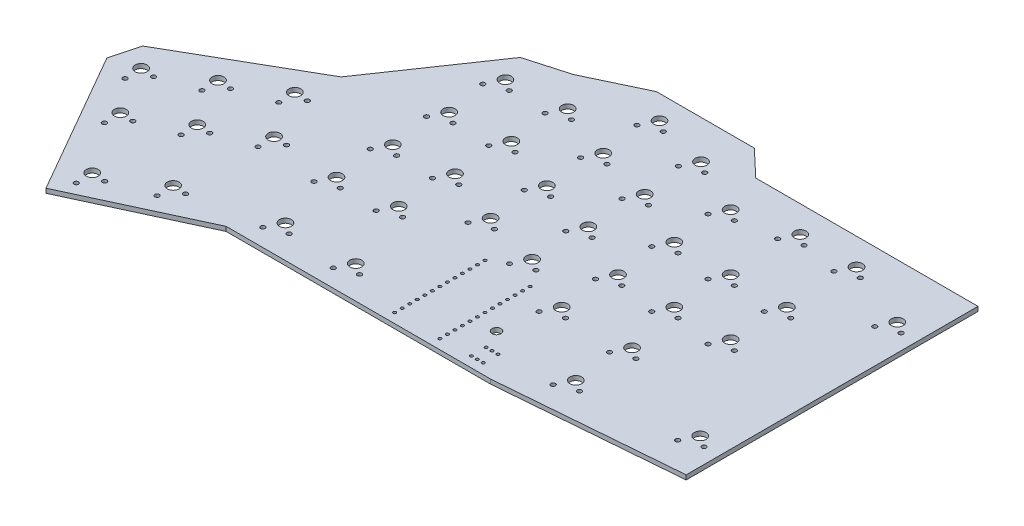
SolidWorks part; units mm, degrees
ref_plane "Front Plane" through (0, 0, 0) normal (0, 0, 1) x (1, 0, 0)
ref_plane "Top Plane" through (0, 0, 0) normal (0, 1, 0) x (1, 0, 0)
ref_plane "Right Plane" through (0, 0, 0) normal (1, 0, 0) x (0, 0, -1)
sketch "Main" plane through (0, 0, 0) normal (0, 1, 0) x (1, 0, 0)
  line L0 (6.46, 3.92) -> (12.81, 6.46) construction
  line L1 (0, 0) -> (18, 0) construction
  line L2 (0, 0) -> (0, 18) construction
  line L3 (0, 18) -> (18, 18) construction
  line L4 (18, 0) -> (18, 18) construction
  line L5 (2, 16) -> (16, 16)
  line L6 (2, 16) -> (2, 2)
  line L7 (2, 2) -> (16, 2)
  line L8 (16, 16) -> (16, 2)
  line L18 (9, 9) -> (6.46, 3.92) construction
  line L20 (9, 9) -> (12.81, 6.46) construction
  line L22 (25.46, 5.92) -> (31.81, 8.46) construction
  line L23 (19, 2) -> (37, 2) construction
  line L24 (19, 2) -> (19, 20) construction
  line L25 (19, 20) -> (37, 20) construction
  line L26 (37, 2) -> (37, 20) construction
  line L27 (21, 18) -> (35, 18)
  line L28 (21, 18) -> (21, 4)
  line L29 (21, 4) -> (35, 4)
  line L30 (35, 18) -> (35, 4)
  line L31 (28, 11) -> (25.46, 5.92) construction
  line L32 (28, 11) -> (31.81, 8.46) construction
  line L33 (44.46, 17.92) -> (50.81, 20.46) construction
  line L34 (38, 14) -> (56, 14) construction
  line L35 (38, 14) -> (38, 32) construction
  line L36 (38, 32) -> (56, 32) construction
  line L37 (56, 14) -> (56, 32) construction
  line L38 (40, 30) -> (54, 30)
  line L39 (40, 30) -> (40, 16)
  line L40 (40, 16) -> (54, 16)
  line L41 (54, 30) -> (54, 16)
  line L42 (47, 23) -> (44.46, 17.92) construction
  line L43 (47, 23) -> (50.81, 20.46) construction
  line L44 (63.46, 12.92) -> (69.81, 15.46) construction
  line L45 (57, 9) -> (75, 9) construction
  line L46 (57, 9) -> (57, 27) construction
  line L47 (57, 27) -> (75, 27) construction
  line L48 (75, 9) -> (75, 27) construction
  line L49 (59, 25) -> (73, 25)
  line L50 (59, 25) -> (59, 11)
  line L51 (59, 11) -> (73, 11)
  line L52 (73, 25) -> (73, 11)
  line L53 (66, 18) -> (63.46, 12.92) construction
  line L54 (66, 18) -> (69.81, 15.46) construction
  line L55 (82.46, 3.92) -> (88.81, 6.46) construction
  line L56 (76, 0) -> (94, 0) construction
  line L57 (76, 0) -> (76, 18) construction
  line L58 (76, 18) -> (94, 18) construction
  line L59 (94, 0) -> (94, 18) construction
  line L60 (78, 16) -> (92, 16)
  line L61 (78, 16) -> (78, 2)
  line L62 (78, 2) -> (92, 2)
  line L63 (92, 16) -> (92, 2)
  line L64 (85, 9) -> (82.46, 3.92) construction
  line L65 (85, 9) -> (88.81, 6.46) construction
  line L66 (101.46, -15.08) -> (107.81, -12.54) construction
  line L67 (95, -19) -> (113, -19) construction
  line L68 (95, -19) -> (95, -1) construction
  line L69 (95, -1) -> (113, -1) construction
  line L70 (113, -19) -> (113, -1) construction
  line L71 (97, -3) -> (111, -3)
  line L72 (97, -3) -> (97, -17)
  line L73 (97, -17) -> (111, -17)
  line L74 (111, -3) -> (111, -17)
  line L75 (104, -10) -> (101.46, -15.08) construction
  line L76 (104, -10) -> (107.81, -12.54) construction
  line L77 (120.46, -15.08) -> (126.81, -12.54) construction
  line L78 (114, -19) -> (132, -19) construction
  line L79 (114, -19) -> (114, -1) construction
  line L80 (114, -1) -> (132, -1) construction
  line L81 (132, -19) -> (132, -1) construction
  line L82 (116, -3) -> (130, -3)
  line L83 (116, -3) -> (116, -17)
  line L84 (116, -17) -> (130, -17)
  line L85 (130, -3) -> (130, -17)
  line L86 (123, -10) -> (120.46, -15.08) construction
  line L87 (123, -10) -> (126.81, -12.54) construction
  line L88 (2, -3) -> (16, -3)
  line L89 (2, -3) -> (2, -17)
  line L90 (2, -17) -> (16, -17)
  line L91 (16, -3) -> (16, -17)
  line L92 (21, -1) -> (35, -1)
  line L93 (21, -1) -> (21, -15)
  line L94 (21, -15) -> (35, -15)
  line L95 (35, -1) -> (35, -15)
  line L96 (40, 11) -> (54, 11)
  line L97 (40, 11) -> (40, -3)
  line L98 (40, -3) -> (54, -3)
  line L99 (54, 11) -> (54, -3)
  line L100 (59, 6) -> (73, 6)
  line L101 (59, 6) -> (59, -8)
  line L102 (59, -8) -> (73, -8)
  line L103 (73, 6) -> (73, -8)
  line L104 (78, -3) -> (92, -3)
  line L105 (78, -3) -> (78, -17)
  line L106 (78, -17) -> (92, -17)
  line L107 (92, -3) -> (92, -17)
  line L108 (97, -22) -> (111, -22)
  line L109 (97, -22) -> (97, -36)
  line L110 (97, -36) -> (111, -36)
  line L111 (111, -22) -> (111, -36)
  line L112 (116, -22) -> (130, -22)
  line L113 (116, -22) -> (116, -36)
  line L114 (116, -36) -> (130, -36)
  line L115 (130, -22) -> (130, -36)
  line L116 (6.46, -15.08) -> (12.81, -12.54) construction
  line L117 (0, -19) -> (18, -19) construction
  line L118 (0, -19) -> (0, -1) construction
  line L119 (0, -1) -> (18, -1) construction
  line L120 (18, -19) -> (18, -1) construction
  line L121 (9, -10) -> (6.46, -15.08) construction
  line L122 (9, -10) -> (12.81, -12.54) construction
  line L123 (25.46, -13.08) -> (31.81, -10.54) construction
  line L124 (19, -17) -> (37, -17) construction
  line L125 (19, -17) -> (19, 1) construction
  line L126 (19, 1) -> (37, 1) construction
  line L127 (37, -17) -> (37, 1) construction
  line L128 (28, -8) -> (25.46, -13.08) construction
  line L129 (28, -8) -> (31.81, -10.54) construction
  line L130 (44.46, -1.08) -> (50.81, 1.46) construction
  line L131 (38, -5) -> (56, -5) construction
  line L132 (38, -5) -> (38, 13) construction
  line L133 (38, 13) -> (56, 13) construction
  line L134 (56, -5) -> (56, 13) construction
  line L135 (47, 4) -> (44.46, -1.08) construction
  line L136 (47, 4) -> (50.81, 1.46) construction
  line L137 (63.46, -6.08) -> (69.81, -3.54) construction
  line L138 (57, -10) -> (75, -10) construction
  line L139 (57, -10) -> (57, 8) construction
  line L140 (57, 8) -> (75, 8) construction
  line L141 (75, -10) -> (75, 8) construction
  line L142 (66, -1) -> (63.46, -6.08) construction
  line L143 (66, -1) -> (69.81, -3.54) construction
  line L144 (82.46, -15.08) -> (88.81, -12.54) construction
  line L145 (76, -19) -> (94, -19) construction
  line L146 (76, -19) -> (76, -1) construction
  line L147 (76, -1) -> (94, -1) construction
  line L148 (94, -19) -> (94, -1) construction
  line L149 (85, -10) -> (82.46, -15.08) construction
  line L150 (85, -10) -> (88.81, -12.54) construction
  line L151 (101.46, -34.08) -> (107.81, -31.54) construction
  line L152 (95, -38) -> (113, -38) construction
  line L153 (95, -38) -> (95, -20) construction
  line L154 (95, -20) -> (113, -20) construction
  line L155 (113, -38) -> (113, -20) construction
  line L156 (104, -29) -> (101.46, -34.08) construction
  line L157 (104, -29) -> (107.81, -31.54) construction
  line L158 (120.46, -34.08) -> (126.81, -31.54) construction
  line L159 (114, -38) -> (132, -38) construction
  line L160 (114, -38) -> (114, -20) construction
  line L161 (114, -20) -> (132, -20) construction
  line L162 (132, -38) -> (132, -20) construction
  line L163 (123, -29) -> (120.46, -34.08) construction
  line L164 (123, -29) -> (126.81, -31.54) construction
  line L165 (2, -22) -> (16, -22)
  line L166 (2, -22) -> (2, -36)
  line L167 (2, -36) -> (16, -36)
  line L168 (16, -22) -> (16, -36)
  line L169 (21, -20) -> (35, -20)
  line L170 (21, -20) -> (21, -34)
  line L171 (21, -34) -> (35, -34)
  line L172 (35, -20) -> (35, -34)
  line L173 (40, -8) -> (54, -8)
  line L174 (40, -8) -> (40, -22)
  line L175 (40, -22) -> (54, -22)
  line L176 (54, -8) -> (54, -22)
  line L177 (59, -13) -> (73, -13)
  line L178 (59, -13) -> (59, -27)
  line L179 (59, -27) -> (73, -27)
  line L180 (73, -13) -> (73, -27)
  line L181 (78, -22) -> (92, -22)
  line L182 (78, -22) -> (78, -36)
  line L183 (78, -36) -> (92, -36)
  line L184 (92, -22) -> (92, -36)
  line L193 (6.46, -34.08) -> (12.81, -31.54) construction
  line L194 (0, -38) -> (18, -38) construction
  line L195 (0, -38) -> (0, -20) construction
  line L196 (0, -20) -> (18, -20) construction
  line L197 (18, -38) -> (18, -20) construction
  line L198 (9, -29) -> (6.46, -34.08) construction
  line L199 (9, -29) -> (12.81, -31.54) construction
  line L200 (25.46, -32.08) -> (31.81, -29.54) construction
  line L201 (19, -36) -> (37, -36) construction
  line L202 (19, -36) -> (19, -18) construction
  line L203 (19, -18) -> (37, -18) construction
  line L204 (37, -36) -> (37, -18) construction
  line L205 (28, -27) -> (25.46, -32.08) construction
  line L206 (28, -27) -> (31.81, -29.54) construction
  line L207 (44.46, -20.08) -> (50.81, -17.54) construction
  line L208 (38, -24) -> (56, -24) construction
  line L209 (38, -24) -> (38, -6) construction
  line L210 (38, -6) -> (56, -6) construction
  line L211 (56, -24) -> (56, -6) construction
  line L212 (47, -15) -> (44.46, -20.08) construction
  line L213 (47, -15) -> (50.81, -17.54) construction
  line L214 (63.46, -25.08) -> (69.81, -22.54) construction
  line L215 (57, -29) -> (75, -29) construction
  line L216 (57, -29) -> (57, -11) construction
  line L217 (57, -11) -> (75, -11) construction
  line L218 (75, -29) -> (75, -11) construction
  line L219 (66, -20) -> (63.46, -25.08) construction
  line L220 (66, -20) -> (69.81, -22.54) construction
  line L221 (82.46, -34.08) -> (88.81, -31.54) construction
  line L222 (76, -38) -> (94, -38) construction
  line L223 (76, -38) -> (76, -20) construction
  line L224 (76, -20) -> (94, -20) construction
  line L225 (94, -38) -> (94, -20) construction
  line L226 (85, -29) -> (82.46, -34.08) construction
  line L227 (85, -29) -> (88.81, -31.54) construction
  line L228 (97, 20.5) -> (111, 20.5)
  line L231 (97, 20.5) -> (97, 6.5)
  line L232 (97, 6.5) -> (111, 6.5)
  line L233 (111, 20.5) -> (111, 6.5)
  line L234 (116, 20.5) -> (130, 20.5)
  line L235 (116, 20.5) -> (116, 6.5)
  line L236 (116, 6.5) -> (130, 6.5)
  line L237 (130, 20.5) -> (130, 6.5)
  line L238 (101.46, 8.42) -> (107.81, 10.96) construction
  line L239 (95, 4.5) -> (113, 4.5) construction
  line L240 (95, 4.5) -> (95, 22.5) construction
  line L241 (95, 22.5) -> (113, 22.5) construction
  line L242 (2, -41) -> (16, -41)
  line L243 (2, -41) -> (2, -55)
  line L244 (2, -55) -> (16, -55)
  line L245 (16, -41) -> (16, -55)
  line L246 (21, -39) -> (35, -39)
  line L247 (21, -39) -> (21, -53)
  line L248 (21, -53) -> (35, -53)
  line L249 (35, -39) -> (35, -53)
  line L250 (40, -27) -> (54, -27)
  line L251 (40, -27) -> (40, -41)
  line L252 (40, -41) -> (54, -41)
  line L253 (54, -27) -> (54, -41)
  line L254 (59, -32) -> (73, -32)
  line L255 (59, -32) -> (59, -46)
  line L256 (59, -46) -> (73, -46)
  line L257 (73, -32) -> (73, -46)
  line L258 (78, -41) -> (92, -41)
  line L259 (78, -41) -> (78, -55)
  line L260 (78, -55) -> (92, -55)
  line L261 (92, -41) -> (92, -55)
  line L270 (6.46, -53.08) -> (12.81, -50.54) construction
  line L271 (0, -57) -> (18, -57) construction
  line L272 (0, -57) -> (0, -39) construction
  line L273 (0, -39) -> (18, -39) construction
  line L274 (18, -57) -> (18, -39) construction
  line L275 (9, -48) -> (6.46, -53.08) construction
  line L276 (9, -48) -> (12.81, -50.54) construction
  line L277 (25.46, -51.08) -> (31.81, -48.54) construction
  line L278 (19, -55) -> (37, -55) construction
  line L279 (19, -55) -> (19, -37) construction
  line L280 (19, -37) -> (37, -37) construction
  line L281 (37, -55) -> (37, -37) construction
  line L282 (28, -46) -> (25.46, -51.08) construction
  line L283 (28, -46) -> (31.81, -48.54) construction
  line L284 (44.46, -39.08) -> (50.81, -36.54) construction
  line L285 (38, -43) -> (56, -43) construction
  line L286 (38, -43) -> (38, -25) construction
  line L287 (38, -25) -> (56, -25) construction
  line L288 (56, -43) -> (56, -25) construction
  line L289 (47, -34) -> (44.46, -39.08) construction
  line L290 (47, -34) -> (50.81, -36.54) construction
  line L291 (63.46, -44.08) -> (69.81, -41.54) construction
  line L292 (57, -48) -> (75, -48) construction
  line L293 (57, -48) -> (57, -30) construction
  line L294 (57, -30) -> (75, -30) construction
  line L295 (75, -48) -> (75, -30) construction
  line L296 (66, -39) -> (63.46, -44.08) construction
  line L297 (66, -39) -> (69.81, -41.54) construction
  line L298 (82.46, -53.08) -> (88.81, -50.54) construction
  line L299 (76, -57) -> (94, -57) construction
  line L300 (76, -57) -> (76, -39) construction
  line L301 (76, -39) -> (94, -39) construction
  line L302 (94, -57) -> (94, -39) construction
  line L303 (85, -48) -> (82.46, -53.08) construction
  line L304 (85, -48) -> (88.81, -50.54) construction
  line L305 (113, 4.5) -> (113, 22.5) construction
  line L306 (104, 13.5) -> (101.46, 8.42) construction
  line L307 (104, 13.5) -> (107.81, 10.96) construction
  line L308 (120.46, 8.42) -> (126.81, 10.96) construction
  line L309 (114, 4.5) -> (132, 4.5) construction
  line L310 (114, 4.5) -> (114, 22.5) construction
  line L311 (114, 22.5) -> (132, 22.5) construction
  line L312 (132, 4.5) -> (132, 22.5) construction
  line L313 (123, 13.5) -> (120.46, 8.42) construction
  line L314 (123, 13.5) -> (126.81, 10.96) construction
  line L319 (97, -60) -> (111, -60)
  line L320 (97, -60) -> (97, -74)
  line L321 (97, -74) -> (111, -74)
  line L322 (111, -60) -> (111, -74)
  line L323 (116, -60) -> (130, -60)
  line L324 (116, -60) -> (116, -74)
  line L325 (116, -74) -> (130, -74)
  line L326 (130, -60) -> (130, -74)
  line L327 (101.46, -72.08) -> (107.81, -69.54) construction
  line L328 (95, -76) -> (113, -76) construction
  line L329 (95, -76) -> (95, -58) construction
  line L330 (95, -58) -> (113, -58) construction
  line L331 (113, -76) -> (113, -58) construction
  line L332 (104, -67) -> (101.46, -72.08) construction
  line L333 (104, -67) -> (107.81, -69.54) construction
  line L334 (120.46, -72.08) -> (126.81, -69.54) construction
  line L335 (114, -76) -> (132, -76) construction
  line L336 (114, -76) -> (114, -58) construction
  line L337 (114, -58) -> (132, -58) construction
  line L338 (132, -76) -> (132, -58) construction
  line L339 (123, -67) -> (120.46, -72.08) construction
  line L340 (123, -67) -> (126.81, -69.54) construction
  line L341 (97, -41) -> (111, -41)
  line L342 (97, -41) -> (97, -55)
  line L343 (97, -55) -> (111, -55)
  line L344 (111, -41) -> (111, -55)
  line L345 (116, -41) -> (130, -41)
  line L346 (116, -41) -> (116, -55)
  line L347 (116, -55) -> (130, -55)
  line L348 (130, -41) -> (130, -55)
  line L349 (101.46, -53.08) -> (107.81, -50.54) construction
  line L350 (95, -39) -> (113, -39) construction
  line L351 (113, -57) -> (113, -39) construction
  line L352 (104, -48) -> (101.46, -53.08) construction
  line L353 (104, -48) -> (107.81, -50.54) construction
  line L354 (120.46, -53.08) -> (126.81, -50.54) construction
  line L355 (114, -57) -> (132, -57) construction
  line L356 (114, -57) -> (114, -39) construction
  line L357 (114, -39) -> (132, -39) construction
  line L358 (132, -57) -> (132, -39) construction
  line L359 (123, -48) -> (120.46, -53.08) construction
  line L360 (123, -48) -> (126.81, -50.54) construction
  line L361 (95, -57) -> (113, -57) construction
  line L362 (95, -57) -> (95, -39) construction
  circle A0 centre (9, 9) radius 2 construction
  circle A1 centre (6.46, 3.92) radius 1.5 construction
  circle A2 centre (12.81, 6.46) radius 1.5 construction
  circle A6 centre (28, 11) radius 2 construction
  circle A7 centre (25.46, 5.92) radius 1.5 construction
  circle A8 centre (31.81, 8.46) radius 1.5 construction
  circle A9 centre (47, 23) radius 2 construction
  circle A10 centre (44.46, 17.92) radius 1.5 construction
  circle A11 centre (50.81, 20.46) radius 1.5 construction
  circle A12 centre (66, 18) radius 2 construction
  circle A13 centre (63.46, 12.92) radius 1.5 construction
  circle A14 centre (69.81, 15.46) radius 1.5 construction
  circle A15 centre (85, 9) radius 2 construction
  circle A16 centre (82.46, 3.92) radius 1.5 construction
  circle A17 centre (88.81, 6.46) radius 1.5 construction
  circle A18 centre (104, -10) radius 2 construction
  circle A19 centre (101.46, -15.08) radius 1.5 construction
  circle A20 centre (107.81, -12.54) radius 1.5 construction
  circle A21 centre (123, -10) radius 2 construction
  circle A22 centre (120.46, -15.08) radius 1.5 construction
  circle A23 centre (126.81, -12.54) radius 1.5 construction
  circle A24 centre (9, -10) radius 2 construction
  circle A25 centre (6.46, -15.08) radius 1.5 construction
  circle A26 centre (12.81, -12.54) radius 1.5 construction
  circle A27 centre (28, -8) radius 2 construction
  circle A28 centre (25.46, -13.08) radius 1.5 construction
  circle A29 centre (31.81, -10.54) radius 1.5 construction
  circle A30 centre (47, 4) radius 2 construction
  circle A31 centre (44.46, -1.08) radius 1.5 construction
  circle A32 centre (50.81, 1.46) radius 1.5 construction
  circle A33 centre (66, -1) radius 2 construction
  circle A34 centre (63.46, -6.08) radius 1.5 construction
  circle A35 centre (69.81, -3.54) radius 1.5 construction
  circle A36 centre (85, -10) radius 2 construction
  circle A37 centre (82.46, -15.08) radius 1.5 construction
  circle A38 centre (88.81, -12.54) radius 1.5 construction
  circle A39 centre (104, -29) radius 2 construction
  circle A40 centre (101.46, -34.08) radius 1.5 construction
  circle A41 centre (107.81, -31.54) radius 1.5 construction
  circle A42 centre (123, -29) radius 2 construction
  circle A43 centre (120.46, -34.08) radius 1.5 construction
  circle A44 centre (126.81, -31.54) radius 1.5 construction
  circle A45 centre (9, -29) radius 2 construction
  circle A46 centre (6.46, -34.08) radius 1.5 construction
  circle A47 centre (12.81, -31.54) radius 1.5 construction
  circle A48 centre (28, -27) radius 2 construction
  circle A49 centre (25.46, -32.08) radius 1.5 construction
  circle A50 centre (31.81, -29.54) radius 1.5 construction
  circle A51 centre (47, -15) radius 2 construction
  circle A52 centre (44.46, -20.08) radius 1.5 construction
  circle A53 centre (50.81, -17.54) radius 1.5 construction
  circle A54 centre (66, -20) radius 2 construction
  circle A55 centre (63.46, -25.08) radius 1.5 construction
  circle A56 centre (69.81, -22.54) radius 1.5 construction
  circle A57 centre (85, -29) radius 2 construction
  circle A58 centre (82.46, -34.08) radius 1.5 construction
  circle A59 centre (88.81, -31.54) radius 1.5 construction
  circle A60 centre (104, 13.5) radius 2 construction
  circle A61 centre (101.46, 8.42) radius 1.5 construction
  circle A62 centre (107.81, 10.96) radius 1.5 construction
  circle A63 centre (123, 13.5) radius 2 construction
  circle A64 centre (120.46, 8.42) radius 1.5 construction
  circle A65 centre (126.81, 10.96) radius 1.5 construction
  circle A66 centre (9, -48) radius 2 construction
  circle A67 centre (6.46, -53.08) radius 1.5 construction
  circle A68 centre (12.81, -50.54) radius 1.5 construction
  circle A69 centre (28, -46) radius 2 construction
  circle A70 centre (25.46, -51.08) radius 1.5 construction
  circle A71 centre (31.81, -48.54) radius 1.5 construction
  circle A72 centre (47, -34) radius 2 construction
  circle A73 centre (44.46, -39.08) radius 1.5 construction
  circle A74 centre (50.81, -36.54) radius 1.5 construction
  circle A75 centre (66, -39) radius 2 construction
  circle A76 centre (63.46, -44.08) radius 1.5 construction
  circle A77 centre (69.81, -41.54) radius 1.5 construction
  circle A78 centre (85, -48) radius 2 construction
  circle A79 centre (82.46, -53.08) radius 1.5 construction
  circle A80 centre (88.81, -50.54) radius 1.5 construction
  circle A87 centre (104, -67) radius 2 construction
  circle A88 centre (101.46, -72.08) radius 1.5 construction
  circle A89 centre (107.81, -69.54) radius 1.5 construction
  circle A90 centre (123, -67) radius 2 construction
  circle A91 centre (120.46, -72.08) radius 1.5 construction
  circle A92 centre (126.81, -69.54) radius 1.5 construction
  circle A93 centre (104, -48) radius 2 construction
  circle A94 centre (101.46, -53.08) radius 1.5 construction
  circle A95 centre (107.81, -50.54) radius 1.5 construction
  circle A96 centre (123, -48) radius 2 construction
  circle A97 centre (120.46, -53.08) radius 1.5 construction
  circle A98 centre (126.81, -50.54) radius 1.5 construction
  point P9 (9, 16)
  point P10 (9, 18)
  point P11 (2, 9)
  point P12 (0, 9)
  point P30 (28, 18)
  point P31 (28, 20)
  point P32 (21, 11)
  point P33 (19, 11)
  point P46 (47, 30)
  point P47 (47, 32)
  point P48 (40, 23)
  point P49 (38, 23)
  point P64 (66, 25)
  point P65 (66, 27)
  point P66 (59, 18)
  point P67 (57, 18)
  point P82 (85, 16)
  point P83 (85, 18)
  point P84 (78, 9)
  point P85 (76, 9)
  point P100 (104, -3)
  point P101 (104, -1)
  point P102 (97, -10)
  point P103 (95, -10)
  point P118 (123, -3)
  point P119 (123, -1)
  point P120 (116, -10)
  point P121 (114, -10)
  dimension "D6" = 4
  dimension "D7" = 3
  dimension "D10" = 1
  dimension "D11" = 5
  dimension "D1" = 18
  dimension "D2" = 14
  dimension "D3" = 3.81
  dimension "D4" = 2.54
  dimension "D5" = 2.54
  dimension "D8" = 1
  dimension "D9" = 12
  dimension "D12" = 1
  dimension "D13" = 2
  dimension "D14" = 1
  dimension "D15" = 9
  dimension "D16" = 1
  dimension "D17" = 5.08
  dimension "D18" = 1
  dimension "D20" = 1
  dimension "D22" = 4.5
  dimension "D23" = 2.54
  dimension "D24" = 2.54
  dimension "D25" = 2.54
  dimension "D26" = 2.54
  dimension "D27" = 2.54
  dimension "D28" = 2.54
  dimension "D19" = 4
  dimension "D21" = 2
sketch "EntBckSp" plane through (0, 0, 0) normal (0, 1, 0) x (1, 0, 0)
  line L0 (0, 0) -> (18, 0) construction
  line L1 (139, 11.25) -> (153, 11.25)
  line L2 (139, 11.25) -> (139, -2.75)
  line L3 (139, -2.75) -> (153, -2.75)
  line L4 (153, 11.25) -> (153, -2.75)
  line L5 (137, 18) -> (155, 18) construction
  line L6 (137, 18) -> (137, -9.5) construction
  line L7 (137, -9.5) -> (155, -9.5) construction
  line L8 (155, 18) -> (155, -9.5) construction
  line L9 (2, 2) -> (16, 2) construction
  line L10 (143.46, -0.83) -> (146, 4.25) construction
  line L11 (146, 4.25) -> (149.81, 1.71) construction
  line L12 (149.81, 1.71) -> (143.46, -0.83) construction
  line L13 (6.46, 3.92) -> (12.81, 6.46) construction
  line L14 (9, 9) -> (6.46, 3.92) construction
  line L15 (9, 9) -> (12.81, 6.46) construction
  line L16 (2, -55) -> (16, -55) construction
  line L17 (132, -19) -> (132, -1) construction
  line L18 (101.75, -41) -> (115.75, -41)
  line L19 (101.75, -41) -> (101.75, -55)
  line L20 (101.75, -55) -> (115.75, -55)
  line L21 (115.75, -41) -> (115.75, -55)
  line L22 (95, -39) -> (122.5, -39) construction
  line L23 (95, -39) -> (95, -57) construction
  line L24 (95, -57) -> (122.5, -57) construction
  line L25 (122.5, -39) -> (122.5, -57) construction
  line L26 (106.21, -53.08) -> (108.75, -48) construction
  line L27 (108.75, -48) -> (112.56, -50.54) construction
  line L28 (112.56, -50.54) -> (106.21, -53.08) construction
  line L29 (0, 18) -> (18, 18) construction
  line L30 (46.5, -79) -> (28.5, -79) construction
  line L31 (101.75, -60) -> (115.75, -60)
  line L32 (101.75, -60) -> (101.75, -74)
  line L33 (101.75, -74) -> (115.75, -74)
  line L34 (115.75, -60) -> (115.75, -74)
  line L35 (95, -58) -> (122.5, -58) construction
  line L36 (95, -58) -> (95, -76) construction
  line L37 (95, -76) -> (122.5, -76) construction
  line L38 (122.5, -58) -> (122.5, -76) construction
  line L39 (106.21, -72.08) -> (108.75, -67) construction
  line L40 (108.75, -67) -> (112.56, -69.54) construction
  line L41 (112.56, -69.54) -> (106.21, -72.08) construction
  line L42 (139, -55.25) -> (153, -55.25)
  line L43 (139, -55.25) -> (139, -69.25)
  line L44 (139, -69.25) -> (153, -69.25)
  line L45 (153, -55.25) -> (153, -69.25)
  line L46 (137, -48.5) -> (155, -48.5) construction
  line L47 (137, -48.5) -> (137, -76) construction
  line L48 (137, -76) -> (155, -76) construction
  line L49 (155, -48.5) -> (155, -76) construction
  line L50 (143.46, -67.33) -> (146, -62.25) construction
  line L51 (146, -62.25) -> (149.81, -64.79) construction
  line L52 (149.81, -64.79) -> (143.46, -67.33) construction
  line L64 (95, -38) -> (95, -20) construction
  line L65 (114, -38) -> (132, -38) construction
  line L66 (6.75, -63) -> (20.75, -63)
  line L67 (6.75, -63) -> (6.75, -77)
  line L68 (6.75, -77) -> (20.75, -77)
  line L69 (20.75, -63) -> (20.75, -77)
  line L70 (0, -61) -> (27.5, -61) construction
  line L71 (0, -61) -> (0, -79) construction
  line L72 (0, -79) -> (27.5, -79) construction
  line L73 (27.5, -61) -> (27.5, -79) construction
  line L74 (11.21, -75.08) -> (13.75, -70) construction
  line L75 (13.75, -70) -> (17.56, -72.54) construction
  line L76 (17.56, -72.54) -> (11.21, -75.08) construction
  line L78 (0, -57) -> (0, -39) construction
  line L80 (30.5, -63) -> (44.5, -63)
  line L81 (30.5, -63) -> (30.5, -77)
  line L82 (30.5, -77) -> (44.5, -77)
  line L83 (44.5, -63) -> (44.5, -77)
  line L86 (34.96, -75.08) -> (37.5, -70) construction
  line L87 (37.5, -70) -> (41.31, -72.54) construction
  line L88 (41.31, -72.54) -> (34.96, -75.08) construction
  line L91 (51.25, -61) -> (51.25, -79) construction
  line L92 (23.75, -61) -> (23.75, -79) construction
  line L93 (46.5, -79) -> (46.5, -61) construction
  line L94 (46.5, -61) -> (28.5, -61) construction
  line L95 (28.5, -79) -> (28.5, -61) construction
  circle A0 centre (146, 4.25) radius 2 construction
  circle A1 centre (143.46, -0.83) radius 1.5 construction
  circle A2 centre (149.81, 1.71) radius 1.5 construction
  circle A3 centre (9, 9) radius 2 construction
  circle A4 centre (6.46, 3.92) radius 1.5 construction
  circle A5 centre (108.75, -48) radius 2 construction
  circle A6 centre (106.21, -53.08) radius 1.5 construction
  circle A7 centre (112.56, -50.54) radius 1.5 construction
  circle A8 centre (108.75, -67) radius 2 construction
  circle A9 centre (106.21, -72.08) radius 1.5 construction
  circle A10 centre (112.56, -69.54) radius 1.5 construction
  circle A11 centre (146, -62.25) radius 2 construction
  circle A12 centre (143.46, -67.33) radius 1.5 construction
  circle A13 centre (149.81, -64.79) radius 1.5 construction
  circle A17 centre (13.75, -70) radius 2 construction
  circle A18 centre (11.21, -75.08) radius 1.5 construction
  circle A19 centre (17.56, -72.54) radius 1.5 construction
  circle A20 centre (37.5, -70) radius 2 construction
  circle A21 centre (34.96, -75.08) radius 1.5 construction
  circle A22 centre (41.31, -72.54) radius 1.5 construction
  point P14 (146, 11.25)
  point P15 (146, 18)
  point P16 (139, 4.25)
  point P17 (137, 4.25)
  point P51 (108.75, -41)
  point P52 (108.75, -39)
  point P53 (101.75, -48)
  point P54 (95, -48)
  point P87 (146, -55.25)
  point P88 (146, -48.5)
  point P89 (139, -62.25)
  point P90 (137, -62.25)
  point P105 (13.75, -63)
  point P106 (13.75, -61)
  point P107 (6.75, -70)
  point P108 (0, -70)
  point P109 (37.5, -63)
  point P132 (37.5, -61)
  dimension "D1" = 27.5
  dimension "D2" = 5
  dimension "D3" = 1
  dimension "D5" = 1
  dimension "D6" = 2
  dimension "D7" = 1
  dimension "D8" = 8
  dimension "D9" = 2.54
  dimension "D10" = 2.54
  dimension "D11" = 2.54
  dimension "D12" = 2.54
  dimension "D4" = 2
sketch "MoLng" plane through (0, 0, 0) normal (0, 1, 0) x (1, 0, 0)
  line L0 (-25.7133, -75.4047) -> (-13.5763, -68.4267)
  line L1 (-25.7133, -75.4047) -> (-18.7353, -87.5417)
  line L2 (-13.5763, -68.4267) -> (-6.5983, -80.5637)
  line L3 (-18.7353, -87.5417) -> (-6.5983, -80.5637)
  line L4 (-30.8116, -70.5498) -> (-15.2068, -61.578) construction
  line L5 (-30.8116, -70.5498) -> (-17.1047, -94.3903) construction
  line L6 (-15.2068, -61.578) -> (-1.5, -85.4186) construction
  line L7 (-17.1047, -94.3903) -> (-1.5, -85.4186) construction
  line L8 (-15.2068, -61.578) -> (-17.1047, -94.3903) construction
  line L9 (-25.7133, -75.4047) -> (-6.5983, -80.5637) construction
  line L10 (0, -61) -> (0, -79) construction
  line L11 (0, -79) -> (27.5, -79) construction
  line L12 (6.75, -77) -> (20.75, -77) construction
  line L13 (-16.1558, -77.9842) -> (13.75, -130) construction
  line L14 (-15.8972, -83.6579) -> (-11.5909, -78.3447) construction
  line L15 (-11.5909, -78.3447) -> (-16.1558, -77.9842) construction
  line L16 (-16.1558, -77.9842) -> (-15.8972, -83.6579) construction
  line L17 (17.56, -72.54) -> (11.21, -75.08) construction
  line L18 (11.21, -75.08) -> (13.75, -70) construction
  line L19 (13.75, -70) -> (17.56, -72.54) construction
  line L20 (-43.0519, -85.3733) -> (-30.9149, -78.3953)
  line L21 (-43.0519, -85.3733) -> (-36.0739, -97.5103)
  line L22 (-30.9149, -78.3953) -> (-23.9369, -90.5323)
  line L23 (-36.0739, -97.5103) -> (-23.9369, -90.5323)
  line L24 (-48.1502, -80.5184) -> (-32.5454, -71.5466) construction
  line L25 (-48.1502, -80.5184) -> (-34.4433, -104.3589) construction
  line L26 (-32.5454, -71.5466) -> (-18.8386, -95.3872) construction
  line L27 (-34.4433, -104.3589) -> (-18.8386, -95.3872) construction
  line L28 (-32.5454, -71.5466) -> (-34.4433, -104.3589) construction
  line L29 (-43.0519, -85.3733) -> (-23.9369, -90.5323) construction
  line L31 (-33.2358, -93.6265) -> (-28.9295, -88.3133) construction
  line L32 (-28.9295, -88.3133) -> (-33.4944, -87.9528) construction
  line L33 (-33.4944, -87.9528) -> (-33.2358, -93.6265) construction
  line L38 (-48.9084, -75.1869) -> (-55.8865, -63.0498)
  line L39 (-48.9084, -75.1869) -> (-36.7714, -68.2088)
  line L43 (-55.8865, -63.0498) -> (-43.7494, -56.0718)
  line L51 (-36.7714, -68.2088) -> (-43.7494, -56.0718)
  line L52 (-48.9084, -75.1869) -> (-43.7494, -56.0718) construction
  line L56 (-55.8865, -63.0498) -> (-36.7714, -68.2088) construction
  line L57 (2, -55) -> (16, -55) construction
  line L58 (-46.0703, -71.3031) -> (-41.7641, -65.9898) construction
  line L59 (-41.7641, -65.9898) -> (-46.3289, -65.6293) construction
  line L66 (-46.3289, -65.6293) -> (-46.0703, -71.3031) construction
  line L69 (9, -48) -> (12.81, -50.54) construction
  line L70 (6.46, -53.08) -> (12.81, -50.54) construction
  line L71 (9, -48) -> (6.46, -53.08) construction
  line L73 (-49.6455, -77.9176) -> (-58.6172, -62.3128) construction
  line L104 (-49.6455, -77.9176) -> (-34.0407, -68.9458) construction
  line L134 (-58.6172, -62.3128) -> (-43.0124, -53.3411) construction
  line L135 (-34.0407, -68.9458) -> (-43.0124, -53.3411) construction
  line L136 (-49.6455, -77.9176) -> (-43.0124, -53.3411) construction
  line L137 (-58.6172, -62.3128) -> (-34.0407, -68.9458) construction
  line L158 (0, -57) -> (18, -57) construction
  line L162 (-32.4368, -65.7167) -> (-39.4148, -53.5797)
  line L163 (-32.4368, -65.7167) -> (-20.2998, -58.7387)
  line L170 (-39.4148, -53.5797) -> (-27.2778, -46.6017)
  line L171 (-20.2998, -58.7387) -> (-27.2778, -46.6017)
  line L174 (-32.4368, -65.7167) -> (-27.2778, -46.6017) construction
  line L175 (-39.4148, -53.5797) -> (-20.2998, -58.7387) construction
  line L176 (-29.5987, -61.8329) -> (-25.2924, -56.5197) construction
  line L177 (-25.2924, -56.5197) -> (-29.8573, -56.1592) construction
  line L180 (-29.8573, -56.1592) -> (-29.5987, -61.8329) construction
  line L181 (-33.1738, -68.4474) -> (-42.1455, -52.8427) construction
  line L182 (-33.1738, -68.4474) -> (-17.569, -59.4757) construction
  line L183 (-42.1455, -52.8427) -> (-26.5408, -43.8709) construction
  line L184 (-17.569, -59.4757) -> (-26.5408, -43.8709) construction
  line L185 (-33.1738, -68.4474) -> (-26.5408, -43.8709) construction
  line L190 (-42.1455, -52.8427) -> (-17.569, -59.4757) construction
  line L191 (-15.9651, -56.2465) -> (-22.9431, -44.1095)
  line L192 (-15.9651, -56.2465) -> (-3.8281, -49.2685)
  line L193 (-22.9431, -44.1095) -> (-10.8061, -37.1315)
  line L194 (-3.8281, -49.2685) -> (-10.8061, -37.1315)
  line L195 (-15.9651, -56.2465) -> (-10.8061, -37.1315) construction
  line L196 (-22.9431, -44.1095) -> (-3.8281, -49.2685) construction
  line L197 (-13.127, -52.3627) -> (-8.8208, -47.0495) construction
  line L198 (-8.8208, -47.0495) -> (-13.3856, -46.689) construction
  line L199 (-13.3856, -46.689) -> (-13.127, -52.3627) construction
  line L200 (-16.7021, -58.9772) -> (-25.6738, -43.3725) construction
  line L201 (-16.7021, -58.9772) -> (-1.0974, -50.0055) construction
  line L202 (-25.6738, -43.3725) -> (-10.0691, -34.4008) construction
  line L203 (-1.0974, -50.0055) -> (-10.0691, -34.4008) construction
  line L204 (-16.7021, -58.9772) -> (-10.0691, -34.4008) construction
  line L205 (-25.6738, -43.3725) -> (-1.0974, -50.0055) construction
  line L206 (-41.9069, -49.245) -> (-48.885, -37.108)
  line L207 (-41.9069, -49.245) -> (-29.7699, -42.267)
  line L208 (-48.885, -37.108) -> (-36.7479, -30.13)
  line L209 (-29.7699, -42.267) -> (-36.7479, -30.13)
  line L210 (-41.9069, -49.245) -> (-36.7479, -30.13) construction
  line L211 (-48.885, -37.108) -> (-29.7699, -42.267) construction
  line L212 (-39.0688, -45.3612) -> (-34.7626, -40.048) construction
  line L213 (-34.7626, -40.048) -> (-39.3274, -39.6875) construction
  line L214 (-39.3274, -39.6875) -> (-39.0688, -45.3612) construction
  line L215 (-42.6439, -51.9757) -> (-51.6157, -36.371) construction
  line L216 (-42.6439, -51.9757) -> (-27.0392, -43.004) construction
  line L217 (-51.6157, -36.371) -> (-36.0109, -27.3993) construction
  line L218 (-27.0392, -43.004) -> (-36.0109, -27.3993) construction
  line L219 (-42.6439, -51.9757) -> (-36.0109, -27.3993) construction
  line L220 (-51.6157, -36.371) -> (-27.0392, -43.004) construction
  line L221 (-25.4353, -39.7749) -> (-32.4133, -27.6378)
  line L222 (-25.4353, -39.7749) -> (-13.2982, -32.7968)
  line L223 (-32.4133, -27.6378) -> (-20.2763, -20.6598)
  line L224 (-13.2982, -32.7968) -> (-20.2763, -20.6598)
  line L225 (-25.4353, -39.7749) -> (-20.2763, -20.6598) construction
  line L226 (-32.4133, -27.6378) -> (-13.2982, -32.7968) construction
  line L227 (-22.5972, -35.8911) -> (-18.2909, -30.5778) construction
  line L228 (-18.2909, -30.5778) -> (-22.8558, -30.2173) construction
  line L229 (-22.8558, -30.2173) -> (-22.5972, -35.8911) construction
  line L230 (-26.1723, -42.5056) -> (-35.144, -26.9008) construction
  line L231 (-26.1723, -42.5056) -> (-10.5675, -33.5338) construction
  line L232 (-35.144, -26.9008) -> (-19.5393, -17.9291) construction
  line L233 (-10.5675, -33.5338) -> (-19.5393, -17.9291) construction
  line L234 (-26.1723, -42.5056) -> (-19.5393, -17.9291) construction
  line L235 (-35.144, -26.9008) -> (-10.5675, -33.5338) construction
  line L236 (-58.3786, -58.7152) -> (-65.3566, -46.5782)
  line L237 (-58.3786, -58.7152) -> (-46.2416, -51.7372)
  line L238 (-65.3566, -46.5782) -> (-53.2196, -39.6001)
  line L239 (-46.2416, -51.7372) -> (-53.2196, -39.6001)
  line L240 (-58.3786, -58.7152) -> (-53.2196, -39.6001) construction
  line L241 (-65.3566, -46.5782) -> (-46.2416, -51.7372) construction
  line L242 (-55.5405, -54.8314) -> (-51.2343, -49.5181) construction
  line L243 (-51.2343, -49.5181) -> (-55.7991, -49.1577) construction
  line L244 (-55.7991, -49.1577) -> (-55.5405, -54.8314) construction
  line L245 (-59.1156, -61.4459) -> (-68.0873, -45.8412) construction
  line L246 (-59.1156, -61.4459) -> (-43.5109, -52.4742) construction
  line L247 (-68.0873, -45.8412) -> (-52.4826, -36.8694) construction
  line L248 (-43.5109, -52.4742) -> (-52.4826, -36.8694) construction
  line L249 (-59.1156, -61.4459) -> (-52.4826, -36.8694) construction
  line L250 (-68.0873, -45.8412) -> (-43.5109, -52.4742) construction
  circle A0 centre (13.75, -130) radius 60 construction
  circle A1 centre (-16.1558, -77.9842) radius 2 construction
  circle A2 centre (13.75, -70) radius 2 construction
  circle A3 centre (-15.8972, -83.6579) radius 1.5 construction
  circle A4 centre (-11.5909, -78.3447) radius 1.5 construction
  circle A5 centre (11.21, -75.08) radius 1.5 construction
  circle A6 centre (-33.4944, -87.9528) radius 2 construction
  circle A7 centre (-33.2358, -93.6265) radius 1.5 construction
  circle A8 centre (-28.9295, -88.3133) radius 1.5 construction
  circle A12 centre (-46.3289, -65.6293) radius 2 construction
  circle A13 centre (-46.0703, -71.3031) radius 1.5 construction
  circle A14 centre (-41.7641, -65.9898) radius 1.5 construction
  circle A15 centre (6.46, -53.08) radius 1.5 construction
  circle A16 centre (9, -48) radius 2 construction
  circle A17 centre (-29.8573, -56.1592) radius 2 construction
  circle A18 centre (-25.2924, -56.5197) radius 1.5 construction
  circle A19 centre (-29.5987, -61.8329) radius 1.5 construction
  circle A20 centre (-13.3856, -46.689) radius 2 construction
  circle A24 centre (-8.8208, -47.0495) radius 1.5 construction
  circle A25 centre (-13.127, -52.3627) radius 1.5 construction
  circle A26 centre (-39.3274, -39.6875) radius 2 construction
  circle A27 centre (-34.7626, -40.048) radius 1.5 construction
  circle A28 centre (-39.0688, -45.3612) radius 1.5 construction
  circle A29 centre (-22.8558, -30.2173) radius 2 construction
  circle A30 centre (-18.2909, -30.5778) radius 1.5 construction
  circle A31 centre (-22.5972, -35.8911) radius 1.5 construction
  circle A32 centre (-55.7991, -49.1577) radius 2 construction
  circle A35 centre (-51.2343, -49.5181) radius 1.5 construction
  circle A36 centre (-55.5405, -54.8314) radius 1.5 construction
  point P2 (-16.1558, -77.9842)
  point P11 (-16.1558, -77.9842)
  point P28 (-46.3289, -65.6293)
  point P39 (-33.4944, -87.9528)
  point P46 (-33.4944, -87.9528)
  point P89 (-29.8573, -56.1592)
  point P112 (-13.3856, -46.689)
  point P134 (-39.3274, -39.6875)
  point P155 (-22.8558, -30.2173)
  point P170 (-55.7991, -49.1577)
  dimension "D1" = 120
  dimension "D2" = 2
  dimension "D4" = 2
  dimension "D5" = 3
  dimension "D6" = 1.5
  dimension "D8" = 1
  dimension "D10" = 21.08
  dimension "D11" = 21.08
  dimension "D9" = 21.08
  dimension "D3" = 3
  dimension "D7" = 1
sketch "Sketch2" plane through (0, 0, 0) normal (0, 1, 0) x (1, 0, 0)
  line L0 (71, 31) -> (38, 31)
  line L1 (38, 31) -> (19, 22)
  line L2 (19, 22) -> (5, 18)
  line L3 (5, 18) -> (-19.5393, -17.9291)
  line L4 (-19.5393, -17.9291) -> (-62.0188, -42.3521)
  line L5 (-64.5983, -51.9097) -> (-36.8109, -100.241)
  line L6 (-48.1502, -80.5184) -> (-34.4433, -104.3589) construction
  line L7 (-36.8109, -100.241) -> (4.75, -81)
  line L8 (4.75, -81) -> (94, -81)
  line L9 (94, -81) -> (155, -76)
  line L10 (155, -76) -> (155, 22.5)
  line L11 (155, 22.5) -> (80, 22.5)
  line L12 (80, 22.5) -> (71, 31)
  line L13 (6.75, -63) -> (6.75, -77) construction
  line L14 (38, 32) -> (56, 32) construction
  line L15 (0, -79) -> (27.5, -79) construction
  line L16 (-36.0739, -97.5103) -> (-23.9369, -90.5323) construction
  line L17 (0, 18) -> (18, 18) construction
  line L18 (-62.0188, -42.3521) -> (-64.5983, -51.9097)
  line L19 (94, -38) -> (94, -20) construction
  line L20 (-68.0873, -45.8412) -> (-52.4826, -36.8694) construction
  line L21 (-59.1156, -61.4459) -> (-68.0873, -45.8412) construction
  line L22 (95, -76) -> (122.5, -76) construction
  line L23 (155, -48.5) -> (155, -76) construction
  line L24 (114, 22.5) -> (132, 22.5) construction
  line L27 (75, 9) -> (75, 27) construction
  line L28 (38, 14) -> (38, 32) construction
  line L29 (19, 2) -> (19, 20) construction
  line L30 (19, 20) -> (37, 20) construction
  dimension "D1" = 2
  dimension "D2" = 2
  dimension "D3" = 2
  dimension "D4" = 89.25
  dimension "D5" = 45.7987
  dimension "D6" = 61.2046
  dimension "D7" = 98.5
  dimension "D8" = 5
  dimension "D9" = 75
  dimension "D10" = 12.3794
  dimension "D11" = 1
  dimension "D12" = 2
  dimension "D13" = 21.0238
  dimension "D14" = 14.5602
  dimension "D15" = 43.5095
  dimension "D16" = 7
  dimension "D17" = 7
  dimension "D18" = 5
  dimension "D19" = 55.75
  dimension "D20" = 49
  dimension "D21" = 4
extrude "Boss-Extrude1" add sketch "Sketch2" against normal blind 1.5
sketch "Sketch3" plane through (0, 0, 0) normal (0, 1, 0) x (1, 0, 0)
  line L0 (-32.4133, -27.6378) -> (-13.2982, -32.7968) construction
  line L1 (-48.9084, -75.1869) -> (-43.7494, -56.0718) construction
  line L2 (-32.5454, -71.5466) -> (-34.4433, -104.3589) construction
  circle A0 centre (-55.7991, -49.1577) radius 2
  circle A1 centre (-39.3274, -39.6875) radius 2
  circle A2 centre (-22.8558, -30.2173) radius 2
  circle A3 centre (-46.3289, -65.6293) radius 2
  circle A4 centre (-29.8573, -56.1592) radius 2
  circle A5 centre (-13.3856, -46.689) radius 2
  circle A6 centre (-33.4944, -87.9528) radius 2
  circle A7 centre (-16.1558, -77.9842) radius 2
  circle A8 centre (13.75, -70) radius 2
  circle A9 centre (37.5, -70) radius 2
  circle A10 centre (28, -46) radius 2
  circle A11 centre (9, -48) radius 2
  circle A12 centre (9, -29) radius 2
  circle A13 centre (28, -27) radius 2
  circle A14 centre (47, -34) radius 2
  circle A15 centre (66, -39) radius 2
  circle A16 centre (9, -10) radius 2
  circle A17 centre (9, 9) radius 2
  circle A18 centre (28, 11) radius 2
  circle A19 centre (47, 23) radius 2
  circle A20 centre (47, 4) radius 2
  circle A21 centre (28, -8) radius 2
  circle A22 centre (47, -15) radius 2
  circle A23 centre (66, 18) radius 2
  circle A24 centre (66, -1) radius 2
  circle A25 centre (66, -20) radius 2
  circle A26 centre (85, 9) radius 2
  circle A27 centre (104, 13.5) radius 2
  circle A28 centre (123, 13.5) radius 2
  circle A29 centre (146, 4.25) radius 2
  circle A30 centre (123, -10) radius 2
  circle A31 centre (104, -10) radius 2
  circle A32 centre (85, -10) radius 2
  circle A33 centre (85, -29) radius 2
  circle A34 centre (104, -29) radius 2
  circle A35 centre (123, -29) radius 2
  circle A36 centre (85, -48) radius 2
  circle A37 centre (108.75, -48) radius 2
  circle A38 centre (108.75, -67) radius 2
  circle A39 centre (146, -62.25) radius 2
  circle A40 centre (146, 4.25) radius 2 construction
extrude "Cut-Extrude1" cut sketch "Sketch3" against normal through all
sketch "Sketch4" plane through (0, 0, 0) normal (0, 1, 0) x (1, 0, 0)
  circle A0 centre (-55.5405, -54.8314) radius 0.75
  circle A1 centre (-51.2343, -49.5181) radius 0.75
  circle A2 centre (-39.0688, -45.3612) radius 0.75
  circle A3 centre (-34.7626, -40.048) radius 0.75
  circle A4 centre (-22.5972, -35.8911) radius 0.75
  circle A5 centre (-18.2909, -30.5778) radius 0.75
  circle A6 centre (25.46, -51.08) radius 0.75
  circle A7 centre (149.81, 1.71) radius 0.75
  circle A8 centre (143.46, -0.83) radius 0.75
  circle A10 centre (120.46, 8.42) radius 0.75
  circle A11 centre (126.81, 10.96) radius 0.75
  circle A12 centre (126.81, -12.54) radius 0.75
  circle A13 centre (120.46, -15.08) radius 0.75
  circle A14 centre (143.46, -67.33) radius 0.75
  circle A15 centre (149.81, -64.79) radius 0.75
  circle A16 centre (126.81, -31.54) radius 0.75
  circle A17 centre (120.46, -34.08) radius 0.75
  circle A18 centre (107.81, -31.54) radius 0.75
  circle A19 centre (101.46, -34.08) radius 0.75
  circle A20 centre (106.21, -53.08) radius 0.75
  circle A21 centre (112.56, -50.54) radius 0.75
  circle A22 centre (112.56, -69.54) radius 0.75
  circle A23 centre (106.21, -72.08) radius 0.75
  circle A24 centre (107.81, 10.96) radius 0.75
  circle A25 centre (101.46, 8.42) radius 0.75
  circle A26 centre (107.81, -12.54) radius 0.75
  circle A27 centre (101.46, -15.08) radius 0.75
  circle A28 centre (88.81, -12.54) radius 0.75
  circle A29 centre (82.46, -15.08) radius 0.75
  circle A30 centre (82.46, 3.92) radius 0.75
  circle A31 centre (88.81, 6.46) radius 0.75
  circle A32 centre (88.81, -31.54) radius 0.75
  circle A33 centre (82.46, -34.08) radius 0.75
  circle A34 centre (69.81, 15.46) radius 0.75
  circle A35 centre (63.46, 12.92) radius 0.75
  circle A36 centre (69.81, -3.54) radius 0.75
  circle A37 centre (63.46, -6.08) radius 0.75
  circle A38 centre (69.81, -22.54) radius 0.75
  circle A39 centre (63.46, -25.08) radius 0.75
  circle A40 centre (63.46, -44.08) radius 0.75
  circle A41 centre (69.81, -41.54) radius 0.75
  circle A42 centre (88.81, -50.54) radius 0.75
  circle A43 centre (82.46, -53.08) radius 0.75
  circle A44 centre (41.31, -72.54) radius 0.75
  circle A45 centre (34.96, -75.08) radius 0.75
  circle A46 centre (31.81, -48.54) radius 0.75
  circle A47 centre (44.46, -39.08) radius 0.75
  circle A48 centre (50.81, -36.54) radius 0.75
  circle A49 centre (44.46, -20.08) radius 0.75
  circle A50 centre (50.81, -17.54) radius 0.75
  circle A51 centre (31.81, -29.54) radius 0.75
  circle A52 centre (25.46, -32.08) radius 0.75
  circle A53 centre (25.46, -13.08) radius 0.75
  circle A54 centre (31.81, -10.54) radius 0.75
  circle A55 centre (12.81, -12.54) radius 0.75
  circle A56 centre (6.46, -15.08) radius 0.75
  circle A57 centre (6.46, 3.92) radius 0.75
  circle A58 centre (12.81, 6.46) radius 0.75
  circle A59 centre (25.46, 5.92) radius 0.75
  circle A60 centre (31.81, 8.46) radius 0.75
  circle A61 centre (44.46, 17.92) radius 0.75
  circle A62 centre (50.81, 20.46) radius 0.75
  circle A63 centre (50.81, 1.46) radius 0.75
  circle A64 centre (44.46, -1.08) radius 0.75
  circle A65 centre (12.81, -31.54) radius 0.75
  circle A66 centre (6.46, -34.08) radius 0.75
  circle A67 centre (12.81, -50.54) radius 0.75
  circle A68 centre (6.46, -53.08) radius 0.75
  circle A69 centre (17.56, -72.54) radius 0.75
  circle A70 centre (11.21, -75.08) radius 0.75
  circle A71 centre (-8.8208, -47.0495) radius 0.75
  circle A72 centre (-13.127, -52.3627) radius 0.75
  circle A73 centre (-25.2924, -56.5197) radius 0.75
  circle A74 centre (-29.5987, -61.8329) radius 0.75
  circle A75 centre (-41.7641, -65.9898) radius 0.75
  circle A76 centre (-46.0703, -71.3031) radius 0.75
  circle A77 centre (-28.9295, -88.3133) radius 0.75
  circle A78 centre (-33.2358, -93.6265) radius 0.75
  circle A79 centre (-15.8972, -83.6579) radius 0.75
  circle A80 centre (-11.5909, -78.3447) radius 0.75
  dimension "D1" = 1.5
extrude "Cut-Extrude2" cut sketch "Sketch4" against normal through all
sketch "Sketch5" plane through (0, 0, 0) normal (0, 1, 0) x (1, 0, 0)
  line L0 (66, -48) -> (66, -81) construction
  line L1 (57, -48) -> (75, -48) construction
  line L2 (4.75, -81) -> (94, -81) construction
  circle A0 centre (58.38, -77.75) radius 0.5
  circle A1 centre (58.38, -75.21) radius 0.5
  circle A2 centre (58.38, -72.67) radius 0.5
  circle A3 centre (58.38, -70.13) radius 0.5
  circle A4 centre (58.38, -67.59) radius 0.5
  circle A5 centre (58.38, -65.05) radius 0.5
  circle A6 centre (58.38, -62.51) radius 0.5
  circle A7 centre (58.38, -59.97) radius 0.5
  circle A8 centre (58.38, -57.43) radius 0.5
  circle A9 centre (58.38, -54.89) radius 0.5
  circle A10 centre (58.38, -52.35) radius 0.5
  circle A11 centre (58.38, -49.81) radius 0.5
  circle A12 centre (58.38, -47.27) radius 0.5
  circle A13 centre (73.62, -47.27) radius 0.5
  circle A14 centre (73.62, -49.81) radius 0.5
  circle A15 centre (73.62, -52.35) radius 0.5
  circle A16 centre (73.62, -54.89) radius 0.5
  circle A17 centre (73.62, -57.43) radius 0.5
  circle A18 centre (73.62, -59.97) radius 0.5
  circle A19 centre (73.62, -62.51) radius 0.5
  circle A20 centre (73.62, -65.05) radius 0.5
  circle A21 centre (73.62, -67.59) radius 0.5
  circle A22 centre (73.62, -70.13) radius 0.5
  circle A23 centre (73.62, -72.67) radius 0.5
  circle A24 centre (73.62, -75.21) radius 0.5
  circle A25 centre (73.62, -77.75) radius 0.5
  circle A26 centre (66, -39) radius 2 construction
  circle A27 centre (81, -66) radius 1.5
  dimension "D1" = 1
  dimension "D3" = 13
  dimension "D5" = 38.75
  dimension "D6" = 3
  dimension "D7" = 15
  dimension "D2" = 7.62
  dimension "D4" = 2.54
  dimension "D8" = 27
extrude "Cut-Extrude3" cut sketch "Sketch5" against normal through all
sketch "Sketch6" plane through (0, 0, 0) normal (0, 1, 0) x (1, 0, 0)
  line L0 (84, -77.5) -> (86, -77.5) construction
  line L1 (86, -77.5) -> (88, -77.5) construction
  line L2 (84, -72.5) -> (86, -72.5) construction
  line L3 (86, -72.5) -> (88, -72.5) construction
  circle A0 centre (84, -77.5) radius 0.5
  circle A1 centre (88, -77.5) radius 0.5
  circle A2 centre (86, -77.5) radius 0.5
  circle A3 centre (88, -72.5) radius 0.5
  circle A4 centre (84, -72.5) radius 0.5
  circle A5 centre (86, -72.5) radius 0.5
  circle A6 centre (73.62, -77.75) radius 0.5 construction
  dimension "D1" = 10.38
  dimension "D2" = 0.25
  dimension "D4" = 1
  dimension "D3" = 2
  dimension "D5" = 5
extrude "Cut-Extrude4" cut sketch "Sketch6" against normal through all
equation "\"1.k\"=2"
